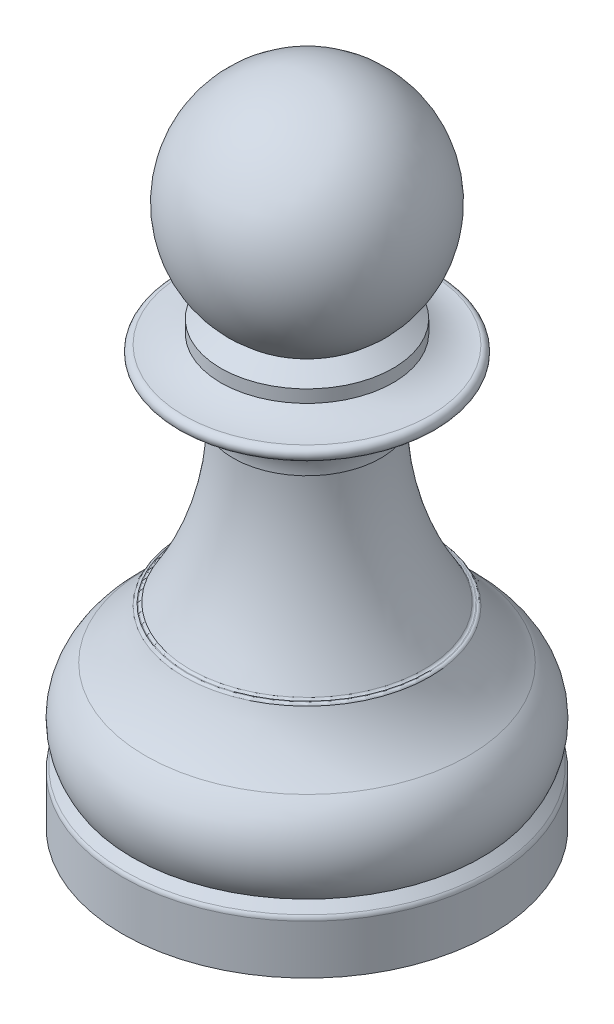
SolidWorks part; units mm, degrees
other "Piece" parameters "D1"=7
ref_plane "Front Plane" through (0, 0, 0) normal (0, 0, 1) x (1, 0, 0)
ref_plane "Top Plane" through (0, 0, 0) normal (0, 1, 0) x (1, 0, 0)
ref_plane "Right Plane" through (0, 0, 0) normal (1, 0, 0) x (0, 0, -1)
sketch "Sketch1" plane through (0, 0, 0) normal (0, 0, 1) x (1, 0, 0)
  line L0 (-15.0008, 0) -> (-15.0008, 4)
  line L1 (-14.2079, 5) -> (-14.8544, 4.3536)
  line L2 (-7, 34.8038) -> (-7, 35.8258)
  line L3 (-5.5, 36.8761) -> (-7, 35.8258)
  line L4 (-10, 33.5) -> (-10, 29) construction
  line L5 (-15.0008, 0) -> (0, 0)
  line L6 (0, 53) -> (0, 0)
  line L7 (0, 0) -> (0, -3.0952) construction
  line L8 (-6, 29) -> (-5.75, 29)
  line L9 (-5.75, 29) -> (-6, 29)
  line L10 (-6, 29) -> (-6, 32.7132) construction
  line L11 (-5.75, 29) -> (-5.75, 35.7914) construction
  line L12 (-9.7727, 15.7558) -> (-9.7123, 15.7558)
  arc A0 (-14.8544, 4.3536) -> (-15.0008, 4) centre (-14.5008, 4) ccw
  arc A1 (-13.1255, 11.6052) -> (-14.2079, 5) centre (-10.0008, 7.7019) ccw
  arc A2 (-13.1255, 11.6052) -> (-10, 15.61) centre (-20, 20.1925) ccw
  arc A3 (-9.7727, 15.7558) -> (-10, 15.61) centre (-9.7727, 15.5058) ccw
  arc A4 (-9.7123, 15.7558) -> (-9.5, 15.8737) centre (-9.7123, 16.0058) ccw
  arc A5 (-9.5, 15.8737) -> (-6.422, 23.2605) centre (-30.5981, 29) ccw
  arc A6 (-6.422, 23.2605) -> (-5.75, 29) centre (-30.5981, 29) ccw
  arc A7 (-6, 29) -> (-6.7812, 31.3748) centre (-10, 29) ccw
  arc A8 (-6.7812, 31.3748) -> (-10, 33) centre (-10, 29) ccw
  arc A9 (-10, 34) -> (-10, 33) centre (-10, 33.5) ccw
  arc A10 (-10, 34) -> (-7, 34.8038) centre (-10, 40) ccw
  arc A11 (0, 53) -> (-5.5, 36.8761) centre (0, 44) ccw
  dimension "D3" = 0.5
  dimension "D8" = 5
  dimension "D12" = 11
  dimension "D15" = 0.25
  dimension "D23" = 10
  dimension "D26" = 0.5
  dimension "D27" = 6
  dimension "D28" = 9
  dimension "D33" = 10
  dimension "D1" = 53
  dimension "D2" = 30.0016
  dimension "D4" = 14.5008
  dimension "D5" = 135
  dimension "D6" = 5
  dimension "D7" = 4
  dimension "D10" = 20
  dimension "D11" = 10.5
  dimension "D13" = 10
  dimension "D14" = 0.25
  dimension "D16" = 5.75
  dimension "D19" = 9.5
  dimension "D24" = 6
  dimension "D29" = 7
  dimension "D30" = 5.5
  dimension "D31" = 55
revolve "Revolve1" add sketch "Sketch1" angle 360 about L7
scale "Scale2" scale about origin uniform scaling yes scale factor 0.766667
sketch "Sketch5" plane through (0, 0, 0) normal (0, -1, 0) x (1, 0, 0)
  point P0 (0, 0)
sketch "Sketch2" plane through (0, 0, 0) normal (0, -1, 0) x (1, 0, 0)
  circle A0 centre (0, 0) radius 10.2
  dimension "D1" = 20.4
extrude "Cut-Extrude1" cut sketch "Sketch2" against normal blind 7
sketch "Sketch6" plane through (0, 7, 0) normal (0, -1, 0) x (1, 0, 0)
  circle A0 centre (0, 0) radius 4.4
  dimension "D1" = 8.8
extrude "Cut-Extrude2" [suppressed] cut sketch "Sketch6" against normal blind 5
sketch "Sketch7" [suppressed] plane through (0, 10, 0) normal (0, -1, 0) x (1, 0, 0)
  circle A0 centre (0, 0) radius 2.2
  dimension "D1" = 4.4
extrude "Cut-Extrude3" [suppressed] cut sketch "Sketch7" against normal blind 13
sketch "Sketch9" plane through (0, 0, 0) normal (0, 0, 1) x (1, 0, 0)
  line L0 (-10.75, 1) -> (0, 1)
  line L1 (-10.75, 1) -> (-10.75, 0)
  line L2 (-10.75, 0) -> (0, 0)
  line L3 (0, 0) -> (0, -1) construction
  line L4 (0, 0) -> (0, 1)
  point P0 (0, 0.75)
  point P4 (-10.2, 0)
  dimension "D1" = 10.2
  dimension "D2" = 1
  dimension "D3" = 0.55
  dimension "D4" = 21.5
revolve "Cut-Revolve1" cut sketch "Sketch9" angle 360 about L3
sketch "Sketch10" plane through (0, 0, 0) normal (0, 0, 1) x (1, 0, 0)
  line L0 (0, 0) -> (-10.55, 0)
  line L1 (0, 0) -> (0, 1)
  line L2 (0, 1) -> (-10.55, 1)
  line L3 (-10.55, 0) -> (-10.55, 1)
  line L4 (0, 0) -> (0, -1.6825) construction
  line L5 (-10.2, 1) -> (-10.2, 0.5)
  line L6 (-10.2, 0.5) -> (0, 0.5)
  dimension "D1" = 21.1
  dimension "D2" = 1
  dimension "D3" = 0.5
  dimension "D4" = 20.4
revolve "Base (White Pawn)" add sketch "Sketch10" angle 360 about L4
equation "\"D1@Cut-Extrude1\"=6mm+1mm"
equation "\"D1@Sketch2\"=20.4mm"
equation "\"PawnHeight\"= 1mm"
equation "\"MagDiam\"= 12mm"
equation "\"MagThickness\"= 3mm"
equation "\"KnightHeight\"= 2.5mm"
equation "\"RookHeight\"= 4mm"
equation "\"BishopHeight\"= 5.5mm"
equation "\"QueenHeight\"= 6.5mm"
equation "\"KingHeight\"= 8mm"
equation "\"WeightOuterDiam\"= 18mm"
equation "\"WeightInnerDiam\"= \"MagDiam\" + 0.3mm"
equation "\"WeightHeight\"= 9mm"
equation "\"BaseOuterDiam\"= 20mm"
equation "\"BaseInnerDiam\"= 12.7mm"
equation "\"FeltThickness\"= 1mm"
equation "\"ThreadedDepth\"= 10mm"
equation "\"TapdrillDiam\"= 4.4mm"
equation "\"SocketDepth\"= 5mm"
equation "\"SocketDiam\"= 8.5mm"
equation "\"D1@Sketch6\"=\"SocketDiam\"+0.3"
equation "\"D1@Cut-Extrude2\"=\"SocketDepth\""
equation "\"D1@Sketch7\"=\"TapdrillDiam\""
equation "\"D1@Cut-Extrude3\"=\"ThreadedDepth\"+3mm"
